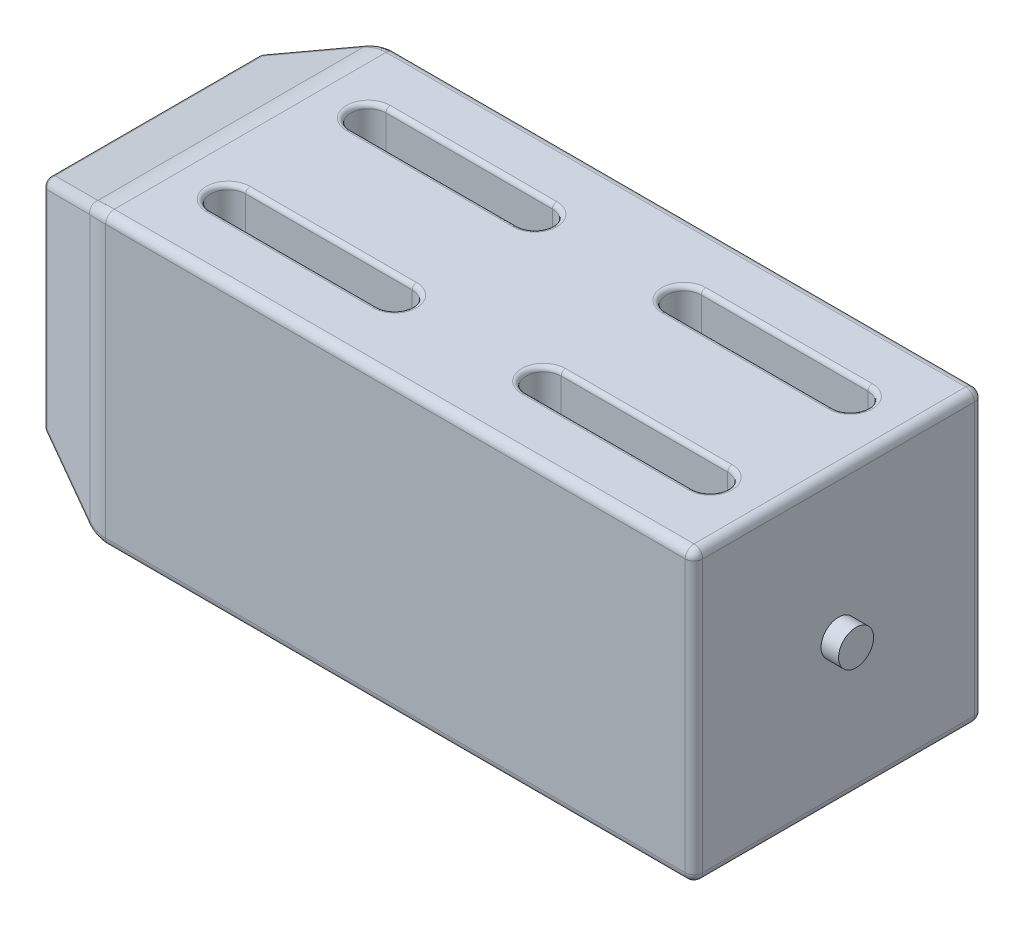
SolidWorks part; units mm, degrees
ref_plane "Ön Düzlem" through (0, 0, 0) normal (0, 0, 1) x (1, 0, 0)
ref_plane "Üst Düzlem" through (0, 0, 0) normal (0, 1, 0) x (1, 0, 0)
ref_plane "Sağ Düzlem" through (0, 0, 0) normal (1, 0, 0) x (0, 0, -1)
sketch "Sketch1" plane through (0, 0, 0) normal (0, 0, 1) x (1, 0, 0)
  line L1 (39.1, 16.5) -> (-39.1, 16.5)
  line L2 (39.1, 16.5) -> (39.1, -16.5)
  line L3 (39.1, -16.5) -> (-39.1, -16.5)
  line L4 (-39.1, 16.5) -> (-39.1, -16.5)
  line L5 (39.1, 16.5) -> (-39.1, -16.5) construction
  line L6 (39.1, -16.5) -> (-39.1, 16.5) construction
  point P0 (0, 0)
  dimension "D1" = 33
  dimension "D2" = 78.2
extrude "Boss-Extrude1" add sketch "Sketch1" along normal mid plane 33
sketch "Sketch3" plane through (-39.1, 0, 0) normal (-1, 0, 0) x (0, 0, 1)
  line L14 (12.5, -12.5) -> (12.5, 12.5)
  line L15 (-12.5, -12.5) -> (12.5, -12.5)
  line L16 (-12.5, 12.5) -> (-12.5, -12.5)
  line L17 (12.5, 12.5) -> (-12.5, 12.5)
  line L18 (12.5, -12.5) -> (12.5, 12.5)
  line L19 (-12.5, -12.5) -> (12.5, -12.5)
  line L20 (-12.5, 12.5) -> (-12.5, -12.5)
  line L21 (12.5, 12.5) -> (-12.5, 12.5)
  dimension "D1" = 4
extrude "Cut-Extrude1" cut sketch "Sketch3" against normal blind 15 draft 22 flip side to cut
sketch "Sketch4" plane through (0, 16.5, 0) normal (0, 1, 0) x (1, 0, 0)
  line L0 (-22.5498, 8) -> (-3.5498, 8) construction
  line L1 (-22.5498, 10) -> (-3.5498, 10)
  line L2 (-22.5498, 6) -> (-3.5498, 6)
  line L3 (4.9502, -16.5) -> (4.9502, 16.5) construction
  line L5 (39.1, -16.5) -> (-29.1997, -16.5) construction
  line L6 (39.1, 16.5) -> (-29.1997, 16.5) construction
  line L7 (32.4502, 8) -> (13.4502, 8) construction
  line L8 (32.4502, 10) -> (13.4502, 10)
  line L9 (32.4502, 6) -> (13.4502, 6)
  arc A0 (-22.5498, 10) -> (-22.5498, 6) centre (-22.5498, 8) ccw
  arc A1 (-3.5498, 6) -> (-3.5498, 10) centre (-3.5498, 8) ccw
  arc A2 (32.4502, 10) -> (32.4502, 6) centre (32.4502, 8) cw
  arc A3 (13.4502, 6) -> (13.4502, 10) centre (13.4502, 8) cw
  point P2 (-13.0498, 8)
  point P17 (22.9502, 8)
  dimension "D1" = 4
  dimension "D2" = 19
  dimension "D3" = 18
  dimension "D4" = 8
extrude "Cut-Extrude2" cut sketch "Sketch4" against normal through all
sketch "Sketch2" plane through (39.1, 0, 0) normal (1, 0, 0) x (0, 0, -1)
  circle A0 centre (0, 0) radius 2
  dimension "D1" = 4
extrude "Boss-Extrude2" add sketch "Sketch2" along normal blind 2 and the other way offset from surface (81.2 mm away) 3 other way up to face at (-39.1, 0, 0)
mirror "Mirror1" about plane through (0, 0, 0) normal (0, 0, 1) of "Cut-Extrude2"
fillet "Fillet2" radius 6 4 edges at (-29.1997, 0, 16.5) (-29.1997, 16.5, 0) (-29.1997, 0, -16.5) (-29.1997, -16.5, 0)
fillet "Fillet3" radius 1 20 edges at (-34.6905, -14.2816, -14.2816) (-29.1782, -16.3898, -16.3898) (5.5333, 16.5, -16.5) (-29.1782, 16.3898, -16.3898) (5.5333, 16.5, 16.5) (-29.1782, 16.3898, 16.3898) (5.5333, -16.5, 16.5) (-29.1782, -16.3898, 16.3898) (39.1, 0, 16.5) (39.1, 16.5, 0) (39.1, -16.5, 0) (39.1, 0, -16.5) (5.5333, -16.5, -16.5) (-34.6905, 14.2816, -14.2816) (-34.6905, 14.2816, 14.2816) (-34.6905, -14.2816, 14.2816) (-39.1, -12.5, 0) (-39.1, 0, -12.5) (-39.1, 0, 12.5) (-39.1, 12.5, 0)
fillet "Fillet4" radius 0.5 32 edges at (-24.5498, -16.5, -8) (-13.0498, -16.5, -10) (-1.5498, -16.5, -8) (-24.5498, 16.5, -8) (-13.0498, 16.5, -10) (-1.5498, 16.5, -8) (11.4502, -16.5, -8) (22.9502, -16.5, -10) (34.4502, -16.5, -8) (11.4502, 16.5, -8) (22.9502, 16.5, -10) (34.4502, 16.5, -8) (34.4502, -16.5, 8) (22.9502, -16.5, 6) (11.4502, -16.5, 8) (34.4502, 16.5, 8) (22.9502, 16.5, 6) (11.4502, 16.5, 8) (-1.5498, -16.5, 8) (-13.0498, -16.5, 6) (-24.5498, -16.5, 8) (-1.5498, 16.5, 8) (-13.0498, 16.5, 6) (-24.5498, 16.5, 8) (-13.0498, -16.5, -6) (-13.0498, 16.5, -6) (22.9502, -16.5, -6) (22.9502, 16.5, -6) (22.9502, -16.5, 10) (22.9502, 16.5, 10) (-13.0498, -16.5, 10) (-13.0498, 16.5, 10)
